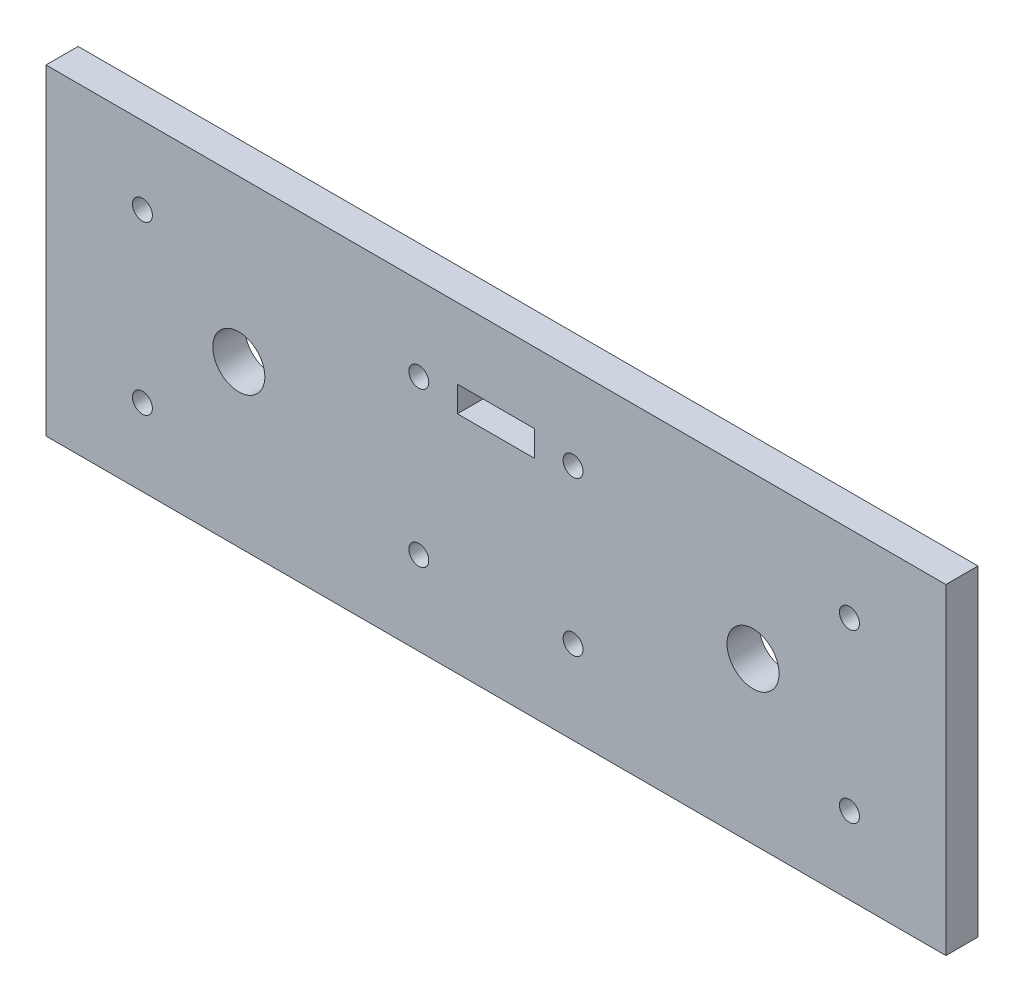
SolidWorks part; units mm, degrees
ref_plane "Plan de face" through (0, 0, 0) normal (0, 0, 1) x (1, 0, 0)
ref_plane "Plan de dessus" through (0, 0, 0) normal (0, 1, 0) x (1, 0, 0)
ref_plane "Plan de droite" through (0, 0, 0) normal (1, 0, 0) x (0, 0, -1)
sketch "Esquisse1" plane through (0, 0, 0) normal (0, 0, 1) x (1, 0, 0)
  line L0 (0, 0) -> (10.6959, 0) construction
  line L1 (-70, -25) -> (70, -25)
  line L2 (-70, -25) -> (-70, 25)
  line L3 (-70, 25) -> (70, 25)
  line L4 (70, -25) -> (70, 25)
  line L5 (-70, -25) -> (70, 25) construction
  line L6 (-70, 25) -> (70, -25) construction
  line L11 (0, 12) -> (0, 0) construction
  line L12 (-6, 10) -> (6, 10)
  line L13 (0, 0) -> (0, -12.4048) construction
  line L14 (-6, 10) -> (-6, 14)
  line L15 (-6, 14) -> (6, 14)
  line L16 (6, 10) -> (6, 14)
  line L17 (-6, 10) -> (6, 14) construction
  line L18 (-6, 14) -> (6, 10) construction
  circle A0 centre (-40, 0) radius 4.05
  circle A6 centre (-55, -13) radius 1.55
  circle A7 centre (-55, 13) radius 1.55
  circle A8 centre (55, -13) radius 1.55
  circle A9 centre (55, 13) radius 1.55
  circle A10 centre (40, 0) radius 4.05
  circle A11 centre (-12, 12) radius 1.55
  circle A12 centre (-12, -12) radius 1.55
  circle A13 centre (12, -12) radius 1.55
  circle A14 centre (12, 12) radius 1.55
  point P0 (0, 0)
  point P5 (0, 0)
  point P8 (0, 12)
  point P36 (0, 0)
  dimension "D3" = 15
  dimension "D4" = 12
  dimension "D5" = 8.1
  dimension "D6" = 3.1
  dimension "D7" = 3.1
  dimension "D1" = 140
  dimension "D2" = 50
  dimension "D8" = 12
  dimension "D9" = 40
  dimension "D10" = 12
  dimension "D11" = 12
  dimension "D12" = 4
  dimension "D13" = 12
  dimension "D14" = 25
extrude "Boss.-Extru.1" add sketch "Esquisse1" against normal blind 5
